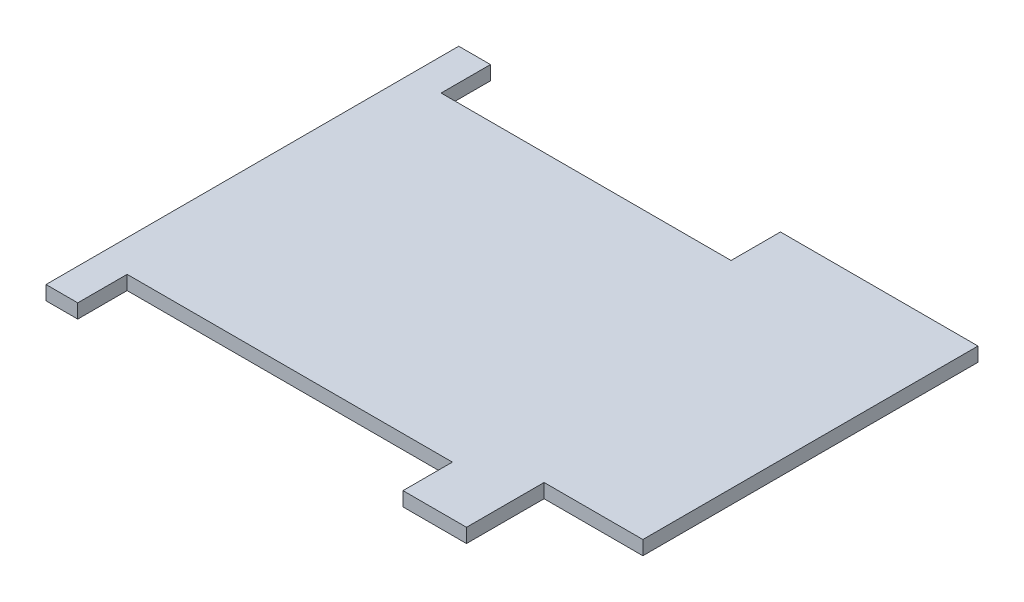
SolidWorks part; units mm, degrees
ref_plane "Спереди" through (0, 0, 0) normal (0, 0, 1) x (1, 0, 0)
ref_plane "Сверху" through (0, 0, 0) normal (0, 1, 0) x (1, 0, 0)
ref_plane "Справа" through (0, 0, 0) normal (1, 0, 0) x (0, 0, -1)
sketch "Эскиз1" plane through (0, 0, 0) normal (0, 1, 0) x (1, 0, 0)
  line L1 (0, 0) -> (73.6, 0)
  line L2 (0, 0) -> (0, -58.5)
  line L3 (0, -58.5) -> (73.6, -58.5)
  line L4 (73.6, 0) -> (73.6, -58.5)
  dimension "D1" = 73.6
  dimension "D2" = 58.5
extrude "Бобышка-Вытянуть1" add sketch "Эскиз1" along normal blind 2
sketch "Эскиз2" plane through (0, 2, 0) normal (0, 1, 0) x (1, 0, 0)
  line L0 (0, -58.5) -> (73.6, -58.5) construction
  line L1 (4.5, 0) -> (45.6, 0)
  line L2 (4.5, 0) -> (4.5, -7)
  line L3 (4.5, -7) -> (45.6, -7)
  line L4 (45.6, 0) -> (45.6, -7)
  line L5 (73.6, -58.5) -> (59.6, -58.5)
  line L6 (73.6, -58.5) -> (73.6, -47.5)
  line L7 (73.6, -47.5) -> (59.6, -47.5)
  line L8 (59.6, -58.5) -> (59.6, -47.5)
  line L9 (4.5, -58.5) -> (50.6, -58.5)
  line L10 (4.5, -58.5) -> (4.5, -51.5)
  line L11 (4.5, -51.5) -> (50.6, -51.5)
  line L12 (50.6, -58.5) -> (50.6, -51.5)
  line L13 (73.6, -58.5) -> (73.6, 0) construction
  line L15 (0, 0) -> (0, -58.5) construction
  point P4 (4.1107, 0)
  point P21 (4.1107, 0)
  dimension "D1" = 14
  dimension "D2" = 11
  dimension "D3" = 7
  dimension "D4" = 46.1
  dimension "D5" = 9
  dimension "D6" = 7
  dimension "D7" = 28
  dimension "D8" = 4.5
  dimension "D9" = 4.5
extrude "Вырез-Вытянуть1" cut sketch "Эскиз2" against normal blind 2
